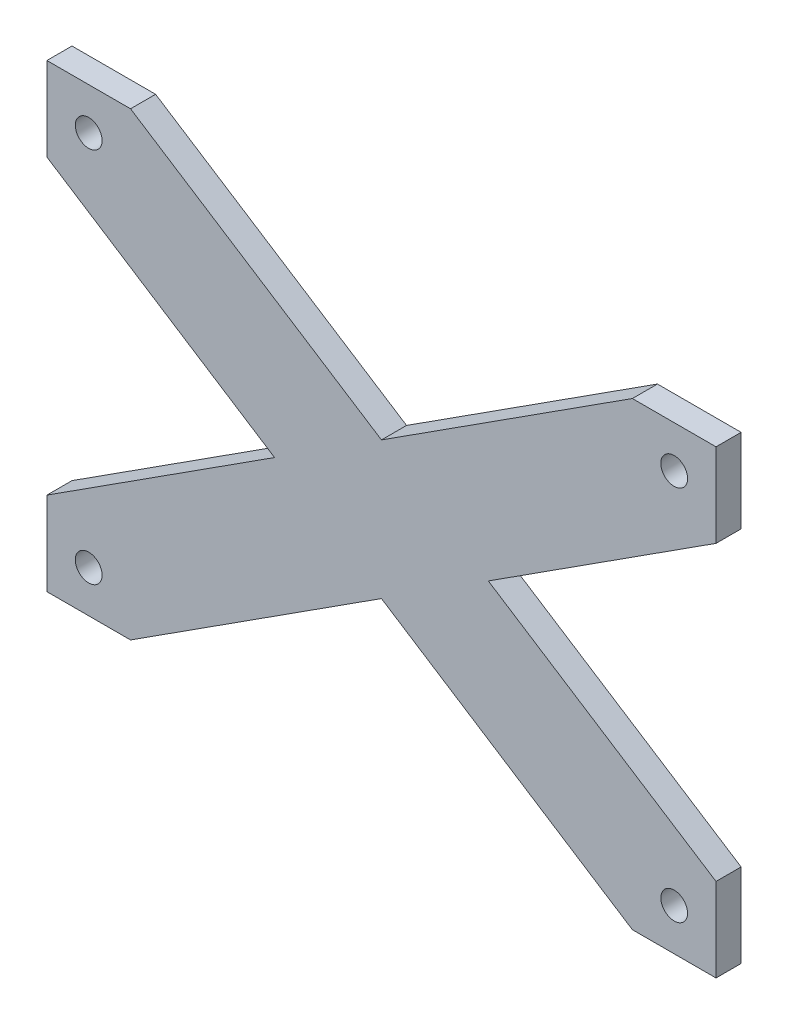
SolidWorks part; units mm, degrees
material "5052-O"
ref_plane "正面" through (0, 0, 0) normal (0, 0, 1) x (1, 0, 0)
ref_plane "平面" through (0, 0, 0) normal (0, 1, 0) x (1, 0, 0)
ref_plane "右側面" through (0, 0, 0) normal (1, 0, 0) x (0, 0, -1)
sketch "ｽｹｯﾁ1" plane through (0, 0, 0) normal (0, 0, 1) x (1, 0, 0)
  line L1 (-40, 27.5) -> (40, 27.5)
  line L2 (-40, 27.5) -> (-40, -27.5)
  line L3 (-40, -27.5) -> (40, -27.5)
  line L4 (40, 27.5) -> (40, -27.5)
  line L5 (-40, 27.5) -> (40, -27.5) construction
  line L6 (-40, -27.5) -> (40, 27.5) construction
  point P0 (0, 0)
  dimension "D1" = 80
  dimension "D2" = 55
extrude "ﾎﾞｽ - 押し出し1" add sketch "ｽｹｯﾁ1" along normal mid plane 3
sketch "ｽｹｯﾁ3" plane through (0, 0, 1.5) normal (0, 0, 1) x (1, 0, 0)
  line L0 (40, 27.5) -> (-40, 27.5) construction
  line L1 (-40, 27.5) -> (-40, -27.5) construction
  line L2 (0, -1.65) -> (0, 1.65) construction
  line L3 (1.65, 0) -> (-1.65, 0) construction
  circle A0 centre (-35, 22.5) radius 1.6
  circle A1 centre (35, 22.5) radius 1.6
  circle A2 centre (35, -22.5) radius 1.6
  circle A3 centre (-35, -22.5) radius 1.6
  dimension "D1" = 3.2
  dimension "D2" = 5
  dimension "D3" = 5
extrude "ｶｯﾄ - 押し出し2" cut sketch "ｽｹｯﾁ3" against normal through all
sketch "ｽｹｯﾁ4" plane through (0, 0, 1.5) normal (0, 0, 1) x (1, 0, 0)
  line L0 (-30, 27.5) -> (40, -17.5)
  line L1 (40, 27.5) -> (-40, 27.5) construction
  line L2 (40, -27.5) -> (40, 27.5) construction
  line L3 (-40, 17.5) -> (30, -27.5)
  line L4 (-40, 27.5) -> (-40, -27.5) construction
  line L6 (-40, -17.5) -> (30, 27.5)
  line L8 (40, 17.5) -> (-30, -27.5)
  line L9 (-40, -27.5) -> (40, -27.5) construction
  dimension "D2" = 10
  dimension "D4" = 10
  dimension "D1" = 10
  dimension "D3" = 0
  dimension "D5" = 10
  dimension "D6" = 10
  dimension "D7" = 10
  dimension "D8" = 0
  dimension "D9" = 10
  dimension "D10" = 10
extrude "ｶｯﾄ - 押し出し3" cut sketch "ｽｹｯﾁ4" against normal blind 10
